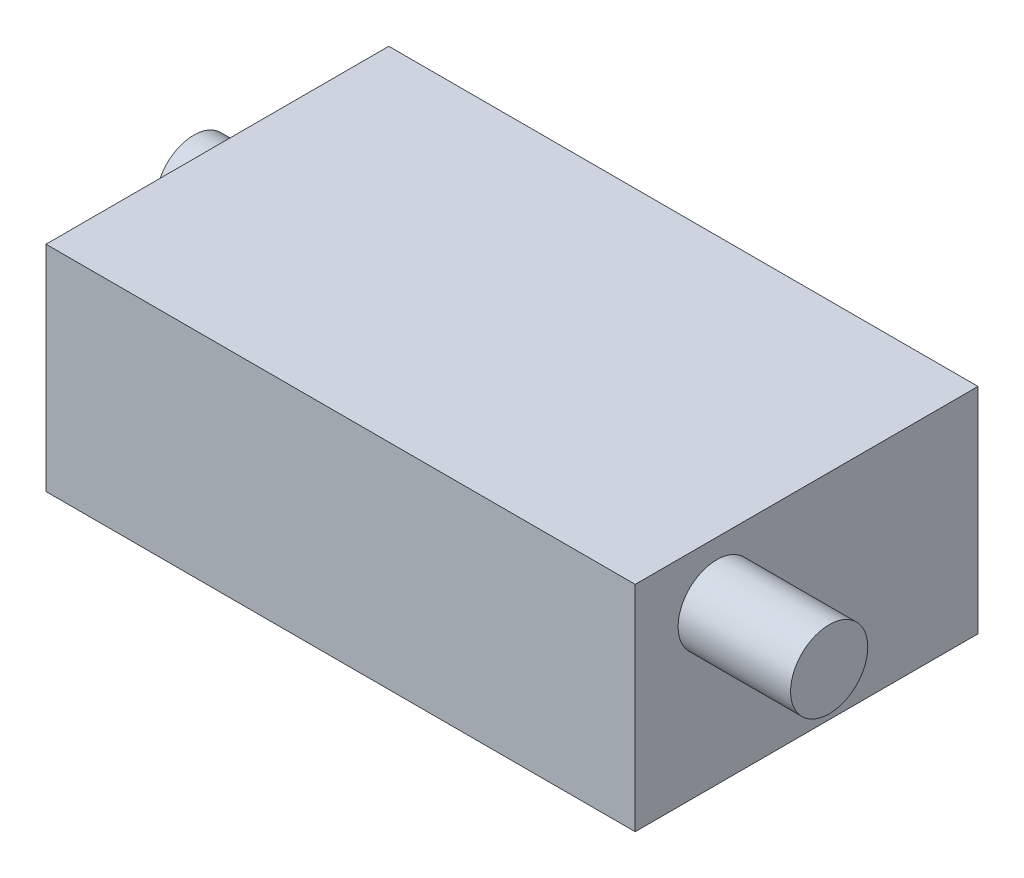
SolidWorks part; units mm, degrees
ref_plane "Front Plane" through (0, 0, 0) normal (0, 0, 1) x (1, 0, 0)
ref_plane "Top Plane" through (0, 0, 0) normal (0, 1, 0) x (1, 0, 0)
ref_plane "Right Plane" through (0, 0, 0) normal (1, 0, 0) x (0, 0, -1)
sketch "Sketch1" plane through (0, 0, 0) normal (1, 0, 0) x (0, 0, -1)
  line L1 (0, 0) -> (60.96, 0)
  line L2 (0, 0) -> (0, 38.1)
  line L3 (0, 38.1) -> (60.96, 38.1)
  line L4 (60.96, 0) -> (60.96, 38.1)
  dimension "D1" = 38.1
  dimension "D2" = 60.96
extrude "Boss-Extrude1" add sketch "Sketch1" along normal blind 104.775
sketch "Sketch2" plane through (104.775, 0, 0) normal (1, 0, 0) x (0, 0, -1)
  circle A0 centre (14.4931, 27.7788) radius 6.8654
sketch "Sketch3" plane through (0, 0, 0) normal (-1, 0, 0) x (0, 0, 1)
  circle A0 centre (-46.281, 15.0277) radius 6.7329
extrude "Boss-Extrude2" add sketch "Sketch3" along normal blind 20.0025
extrude "Boss-Extrude3" add sketch "Sketch2" along normal blind 20.0025
